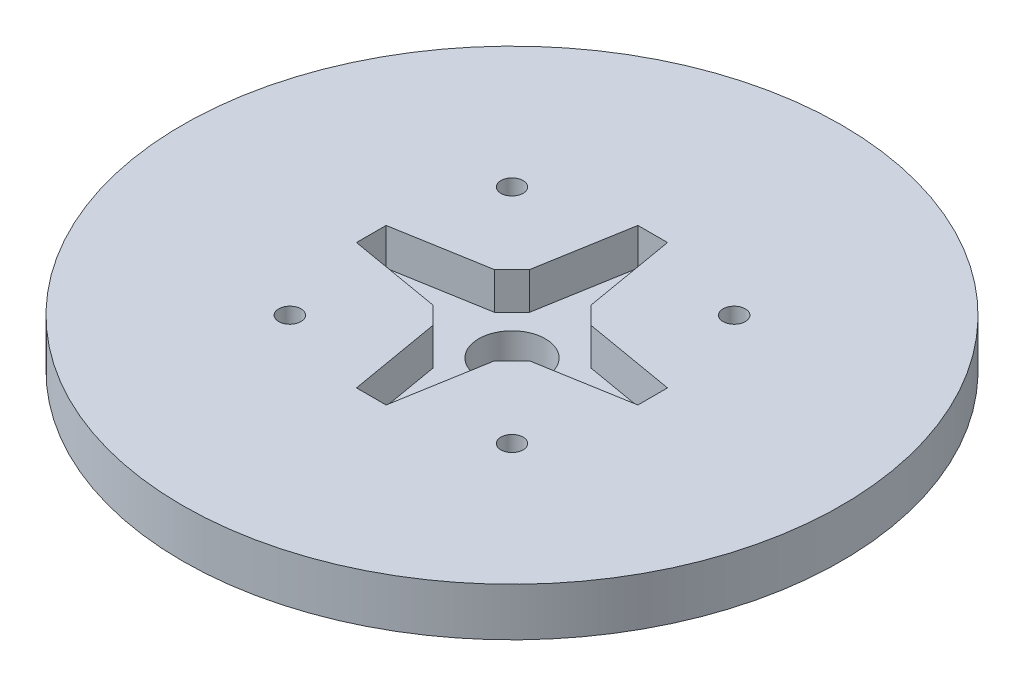
SolidWorks part; units mm, degrees
ref_plane "Front Plane" through (0, 0, 0) normal (0, 0, 1) x (1, 0, 0)
ref_plane "Top Plane" through (0, 0, 0) normal (0, 1, 0) x (1, 0, 0)
ref_plane "Right Plane" through (0, 0, 0) normal (1, 0, 0) x (0, 0, -1)
sketch "Sketch1" plane through (0, 0, 0) normal (0, 1, 0) x (1, 0, 0)
  circle A0 centre (0, 0) radius 44.5
  dimension "D1" = 89
extrude "Boss-Extrude1" add sketch "Sketch1" along normal blind 6.5
sketch "Sketch2" plane through (0, 0, 0) normal (0, 1, 0) x (1, 0, 0)
  circle A0 centre (0, 0) radius 32.5
  dimension "D1" = 65
extrude "Boss-Extrude2" add sketch "Sketch2" against normal blind 8
sketch "Sketch3" plane through (0, 0, 0) normal (0, 1, 0) x (1, 0, 0)
  line L0 (0, 20.6592) -> (0, -17.625) construction
  line L1 (-22.3, 0) -> (28.484, 0) construction
  circle A4 centre (-15, 15) radius 1.5
  circle A5 centre (15, 15) radius 1.5
  circle A6 centre (15, -15) radius 1.5
  circle A7 centre (-15, -15) radius 1.5
  dimension "D1" = 3
  dimension "D2" = 15
  dimension "D3" = 15
extrude "Cut-Extrude1" cut sketch "Sketch3" against normal mid plane 60
sketch "Sketch4" plane through (0, 6.5, 0) normal (0, 1, 0) x (1, 0, 0)
  line L12 (-2, 19) -> (2, 19)
  line L13 (2, 19) -> (4.5, 4.5)
  line L14 (4.5, 4.5) -> (19, 2)
  line L15 (19, 2) -> (19, -2)
  line L16 (0, 28.1485) -> (0, -17.6722) construction
  line L17 (-19, 2) -> (-19, -2)
  line L18 (-4.5, 4.5) -> (-19, 2)
  line L19 (-2, 19) -> (-4.5, 4.5)
  line L20 (-23.5198, 0) -> (30.2783, 0) construction
  line L21 (-2, -19) -> (-4.5, -4.5)
  line L22 (-4.5, -4.5) -> (-19, -2)
  line L23 (4.5, -4.5) -> (19, -2)
  line L24 (2, -19) -> (4.5, -4.5)
  line L25 (-2, -19) -> (2, -19)
  point P11 (0, 19)
  point P13 (0, -19)
  point P18 (-19, 0)
  point P19 (19, 0)
  dimension "D1" = 4.5
  dimension "D2" = 4.5
  dimension "D3" = 0
  dimension "D4" = 0
  dimension "D5" = 19
  dimension "D6" = 19
  dimension "D7" = 2
  dimension "D8" = 2
extrude "Cut-Extrude2" cut sketch "Sketch4" against normal blind 5
sketch "Sketch5" plane through (0, 6.5, 0) normal (0, 1, 0) x (1, 0, 0)
  circle A0 centre (0, 0) radius 4.5
  dimension "D1" = 9
extrude "Cut-Extrude3" cut sketch "Sketch5" against normal blind 9
sketch "Sketch6" plane through (0, 6.5, 0) normal (0, 1, 0) x (1, 0, 0)
  line L0 (-6.5, -4.1552) -> (-6.5, 4.1552)
  line L1 (-4.5, 4.5) -> (-19, 2) construction
  line L2 (-6.5, 4.1552) -> (-4.1552, 6.5)
  line L3 (-2, 19) -> (-4.5, 4.5) construction
  line L4 (-4.1552, 6.5) -> (4.1552, 6.5)
  line L5 (-8.6493, 0) -> (7.9498, 0) construction
  line L6 (-4.1552, -6.5) -> (4.1552, -6.5)
  line L7 (-6.5, -4.1552) -> (-4.1552, -6.5)
  line L8 (0, -7.3642) -> (0, 8.1974) construction
  line L9 (6.5, -4.1552) -> (4.1552, -6.5)
  line L10 (6.5, 4.1552) -> (4.1552, 6.5)
  line L11 (6.5, -4.1552) -> (6.5, 4.1552)
  point P14 (-6.5, 0)
  point P16 (6.5, 0)
  point P19 (0, -6.5)
  point P20 (0, 6.5)
  dimension "D1" = 0
  dimension "D2" = 0
  dimension "D3" = 6.5
  dimension "D4" = 6.5
extrude "Cut-Extrude4" cut sketch "Sketch6" against normal blind 5
